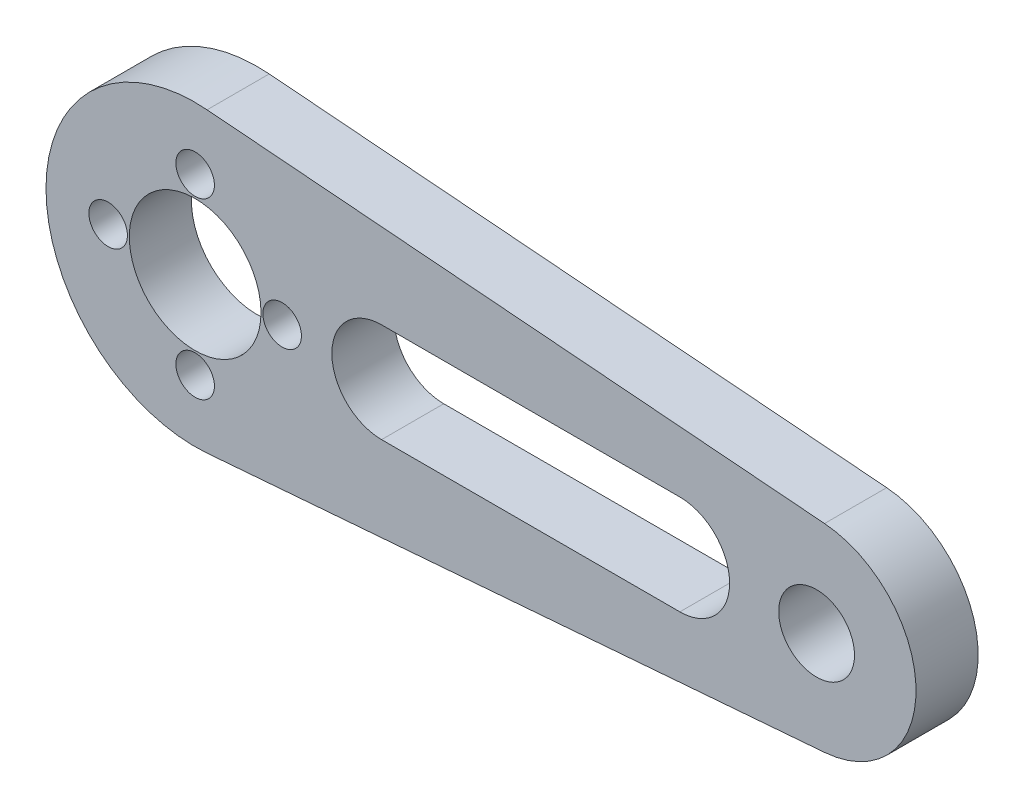
SolidWorks part; units mm, degrees
material "Thornel Mat VMA"
ref_plane "前视基准面" through (0, 0, 0) normal (0, 0, 1) x (1, 0, 0)
ref_plane "上视基准面" through (0, 0, 0) normal (0, 1, 0) x (1, 0, 0)
ref_plane "右视基准面" through (0, 0, 0) normal (1, 0, 0) x (0, 0, -1)
sketch "草图1" plane through (0, 0, 0) normal (0, 0, 1) x (1, 0, 0)
  line L0 (0, 0) -> (50, 0) construction
  line L1 (0.96, 11.9615) -> (50.64, 7.9744)
  line L2 (-7, 0) -> (7, 0) construction
  line L3 (50.64, -7.9744) -> (0.96, -11.9615)
  circle A0 centre (0, 0) radius 5.3
  circle A1 centre (50, 0) radius 3.05
  arc A3 (50.64, -7.9744) -> (50.64, 7.9744) centre (50, 0) ccw
  circle A4 centre (-7, 0) radius 1.55
  circle A5 centre (7, 0) radius 1.55
  arc A6 (0.96, 11.9615) -> (0.96, -11.9615) centre (0, 0) ccw
  circle A7 centre (0, 0) radius 20 construction
  circle A8 centre (0, 0) radius 7 construction
  circle A9 centre (0, 7) radius 1.55
  circle A10 centre (0, -7) radius 1.55
  dimension "D1" = 10.6
  dimension "D3" = 6.1
  dimension "D5" = 3.1
  dimension "D6" = 8
  dimension "D7" = 12
  dimension "D9" = 40
  dimension "D2" = 50
  dimension "D4" = 14
  dimension "D8" = 7
extrude "凸台-拉伸1" add sketch "草图1" along normal blind 5
sketch "草图2" plane through (0, 0, 5) normal (0, 0, 1) x (1, 0, 0)
  line L0 (15, 0) -> (39, 0) construction
  line L1 (15, 4) -> (39, 4)
  line L2 (15, -4) -> (39, -4)
  arc A0 (15, 4) -> (15, -4) centre (15, 0) ccw
  arc A1 (39, -4) -> (39, 4) centre (39, 0) ccw
  circle A2 centre (0, 0) radius 5.3 construction
  circle A3 centre (50, 0) radius 3.05 construction
  point P3 (27, 0)
  dimension "D1" = 4
  dimension "D2" = 15
  dimension "D3" = 11
extrude "切除-拉伸1" cut sketch "草图2" against normal blind 10
